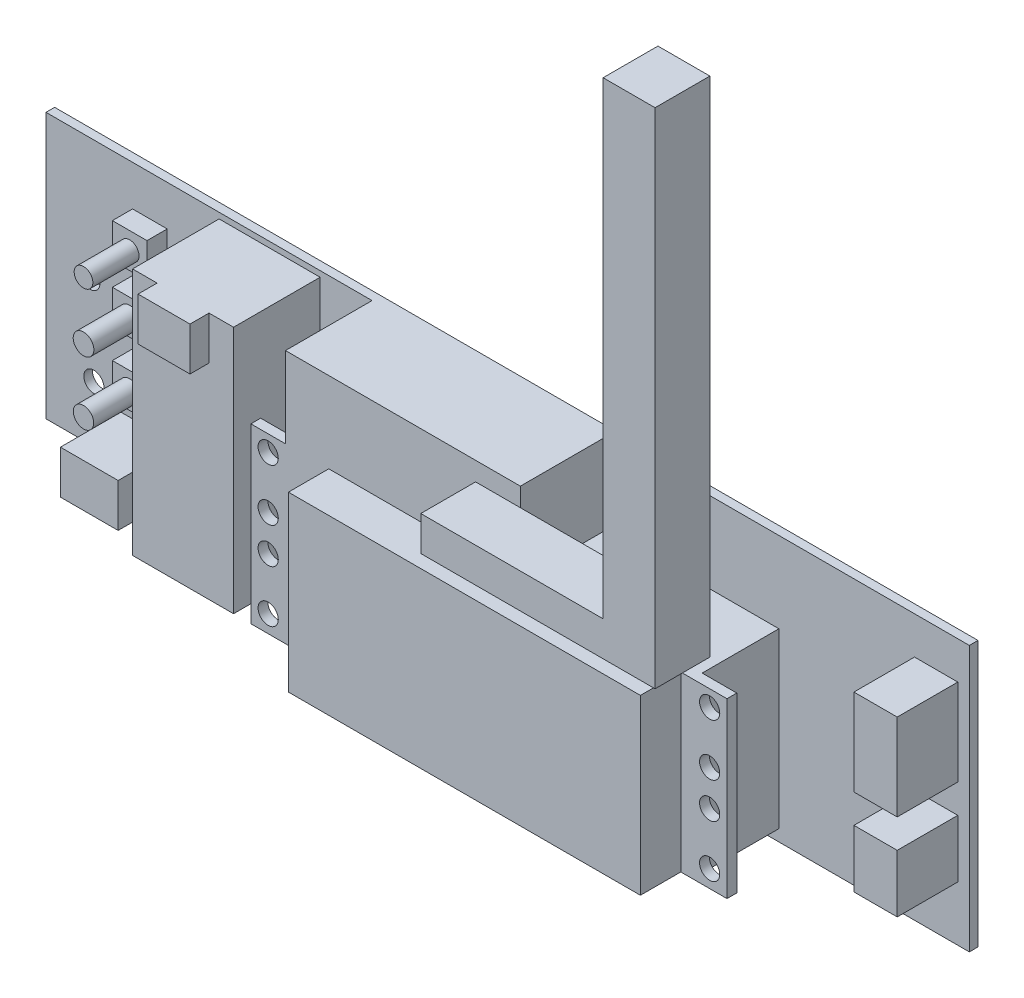
SolidWorks part; units mm, degrees
ref_plane "Přední rovina" through (0, 0, 0) normal (0, 0, 1) x (1, 0, 0)
ref_plane "Horní rovina" through (0, 0, 0) normal (0, 1, 0) x (1, 0, 0)
ref_plane "Pravá rovina" through (0, 0, 0) normal (1, 0, 0) x (0, 0, -1)
sketch "Skica1" plane through (0, 0, 0) normal (0, 0, 1) x (1, 0, 0)
  line L1 (-80, -23) -> (80, -23)
  line L2 (-80, -23) -> (-80, 23)
  line L3 (-80, 23) -> (80, 23)
  line L4 (80, -23) -> (80, 23)
  line L5 (-80, -23) -> (80, 23) construction
  line L6 (-80, 23) -> (80, -23) construction
  point P0 (0, 0)
  dimension "D1" = 160
  dimension "D2" = 46
extrude "Přidat vysunutím1" add sketch "Skica1" along normal blind 1.5
sketch "Skica2" plane through (0, 0, 1.5) normal (0, 0, 1) x (1, 0, 0)
  line L0 (-71.7, -23) -> (-71.7, 23) construction
  line L1 (-80, -23) -> (80, -23) construction
  line L2 (80, 23) -> (-80, 23) construction
  line L3 (62.7, 23) -> (62.7, -23) construction
  line L4 (-80, 23) -> (-80, -23) construction
  line L5 (80, -23) -> (80, 23) construction
  circle A0 centre (-71.7, -13.3) radius 1.75
  circle A1 centre (-72.4, 2) radius 1.75
  circle A2 centre (62.7, 3.2) radius 1.75
  circle A3 centre (62.7, -14.6) radius 1.75
  dimension "D1" = 3.5
  dimension "D2" = 8.3
  dimension "D3" = 7.6
  dimension "D4" = 9.7
  dimension "D5" = 25
  dimension "D6" = 17.3
  dimension "D7" = 8.4
  dimension "D8" = 26.2
extrude "Odebrat vysunutím1" cut sketch "Skica2" against normal through all both and the other way through all
sketch "Skica3" plane through (0, 0, 1.5) normal (0, 0, 1) x (1, 0, 0)
  line L0 (-80, -23) -> (80, -23) construction
  line L1 (-67, -23) -> (-57, -23)
  line L2 (-67, -23) -> (-67, -15.5)
  line L3 (-67, -15.5) -> (-57, -15.5)
  line L4 (-57, -23) -> (-57, -15.5)
  line L5 (80, -23) -> (80, 23) construction
  line L6 (78, -13.5) -> (70.5, -13.5)
  line L7 (78, -13.5) -> (78, -3.5)
  line L8 (78, -3.5) -> (70.5, -3.5)
  line L9 (70.5, -13.5) -> (70.5, -3.5)
  line L10 (78, 1.5) -> (70.5, 1.5)
  line L11 (78, 1.5) -> (78, 16.5)
  line L12 (78, 16.5) -> (70.5, 16.5)
  line L13 (70.5, 1.5) -> (70.5, 16.5)
  dimension "D1" = 7.5
  dimension "D2" = 10
  dimension "D3" = 13
  dimension "D4" = 7.5
  dimension "D5" = 7.5
  dimension "D6" = 10
  dimension "D7" = 15
  dimension "D8" = 9.5
  dimension "D9" = 24.5
  dimension "D10" = 2
extrude "Přidat vysunutím2" add sketch "Skica3" along normal blind 10.5
sketch "Skica5" plane through (0, 0, 1.5) normal (0, 0, 1) x (1, 0, 0)
  line L0 (-57, -23) -> (80, -23) construction
  line L1 (-65, -5) -> (-59, -5)
  line L2 (-65, -5) -> (-65, -11)
  line L3 (-65, -11) -> (-59, -11)
  line L4 (-59, -5) -> (-59, -11)
  line L5 (-65, 6) -> (-59, 6)
  line L6 (-65, 6) -> (-65, 0)
  line L7 (-65, 0) -> (-59, 0)
  line L8 (-59, 6) -> (-59, 0)
  line L9 (-65, 16) -> (-59, 16)
  line L10 (-65, 16) -> (-65, 10)
  line L11 (-65, 10) -> (-59, 10)
  line L12 (-59, 16) -> (-59, 10)
  line L13 (-80, 23) -> (-80, -23) construction
  dimension "D2" = 6
  dimension "D3" = 12
  dimension "D4" = 23
  dimension "D5" = 33
  dimension "D8" = 15
extrude "Přidat vysunutím3" add sketch "Skica5" along normal blind 3.5
sketch "Skica6" plane through (0, 0, 5) normal (0, 0, 1) x (1, 0, 0)
  line L0 (-65, 16) -> (-59, 10) construction
  line L1 (-65, 10) -> (-59, 16) construction
  line L2 (-65, 13) -> (-59, 13) construction
  line L3 (-65, 16) -> (-65, 10) construction
  line L4 (-59, 10) -> (-59, 16) construction
  line L5 (-62, 16) -> (-62, 10) construction
  line L6 (-59, 16) -> (-65, 16) construction
  line L7 (-65, 10) -> (-59, 10) construction
  line L8 (-62, 13) -> (-62, -23.1285) construction
  line L9 (-65, -8) -> (-59, -8) construction
  line L10 (-65, -5) -> (-65, -11) construction
  line L11 (-59, -11) -> (-59, -5) construction
  line L12 (-65, 3) -> (-59, 3) construction
  line L13 (-65, 6) -> (-65, 0) construction
  line L14 (-59, 0) -> (-59, 6) construction
  circle A0 centre (-62, 13) radius 1.6204
  circle A1 centre (-62, 3) radius 1.79
  circle A2 centre (-62, -8) radius 1.7657
  point P26 (-62, 13)
extrude "Přidat vysunutím4" add sketch "Skica6" along normal blind 8
sketch "Skica7" plane through (0, 0, 1.5) normal (0, 0, 1) x (1, 0, 0)
  line L0 (-80, 23) -> (-80, -23) construction
  line L1 (-50, -21) -> (-32.5, -21)
  line L2 (-50, -21) -> (-50, 22)
  line L3 (-50, 22) -> (-32.5, 22)
  line L4 (-32.5, -21) -> (-32.5, 22)
  line L5 (-23.5, 9) -> (47, 9)
  line L6 (-23.5, 9) -> (-23.5, -21)
  line L7 (-23.5, -21) -> (47, -21)
  line L8 (47, 9) -> (47, -21)
  line L9 (-57, -23) -> (80, -23) construction
  line L11 (-23.5, 9) -> (17.2, 9)
  line L12 (-23.5, 9) -> (-23.5, 23.5)
  line L13 (-23.5, 23.5) -> (17.2, 23.5)
  line L14 (17.2, 9) -> (17.2, 23.5)
  line M21 (80, 23) -> (-80, 23)
  dimension "D1" = 43
  dimension "D2" = 17.5
  dimension "D3" = 30
  dimension "D4" = 70.5
  dimension "D5" = 30
  dimension "D6" = 56.5
  dimension "D7" = 2
  dimension "D8" = 2
  dimension "D9" = 40.7
  dimension "D10" = 14.5
extrude "Přidat vysunutím5" add sketch "Skica7" along normal blind 15 contours L1 L4 L3 L2 | L8 L5 L6 L7 | L5 L14 L12 M21
sketch "Skica8" plane through (0, 0, 16.5) normal (0, 0, 1) x (1, 0, 0)
  line L0 (-50, 22) -> (-32.5, 22) construction
  line L1 (-45.75, 22) -> (-36.75, 22)
  line L2 (-45.75, 22) -> (-45.75, 14.5)
  line L3 (-45.75, 14.5) -> (-36.75, 14.5)
  line L4 (-36.75, 22) -> (-36.75, 14.5)
  line L5 (-41.25, 22) -> (-41.25, 16.6364) construction
  point P8 (-41.25, 22)
  dimension "D1" = 9
  dimension "D2" = 7.5
extrude "Přidat vysunutím6" add sketch "Skica8" along normal blind 3.3
sketch "Skica13" plane through (0, 0, 16.5) normal (0, 0, 1) x (1, 0, 0)
  line L1 (9.4389, 19.7615) -> (50.0389, 19.7615)
  line L2 (9.4389, 19.7615) -> (9.4389, 13.7615)
  line L3 (9.4389, 13.7615) -> (50.0389, 13.7615)
  line L4 (50.0389, 19.7615) -> (50.0389, 13.7615)
  line L5 (50.0389, 13.7615) -> (41.0389, 13.7615)
  line L6 (50.0389, 13.7615) -> (50.0389, 100.9615)
  line L7 (50.0389, 100.9615) -> (41.0389, 100.9615)
  line L8 (41.0389, 13.7615) -> (41.0389, 100.9615)
  line M7 (17.2, 9) -> (17.2, 23)
  dimension "D1" = 6
  dimension "D2" = 40.6
  dimension "D3" = 9
  dimension "D4" = 87.2
extrude "Přidat vysunutím7" add sketch "Skica13" along normal blind 9.5 contours L3 L8 L1 M7 | L8 L3 L4 L1 | L8 L1 L6 L7 | L2 L3 L1 M7
sketch "Skica14" plane through (0, 0, 16.5) normal (0, 0, 1) x (1, 0, 0)
  line L0 (-23.5, -21) -> (47, -21) construction
  line L1 (45, -21) -> (-16, -21)
  line L2 (45, -21) -> (45, 9)
  line L3 (45, 9) -> (-16, 9)
  line L4 (-16, -21) -> (-16, 9)
  line L5 (47, 9) -> (47, -21) construction
  dimension "D1" = 61
  dimension "D2" = 2
  dimension "D3" = 30
extrude "Přidat vysunutím8" add sketch "Skica14" along normal blind 7
sketch "Skica15" plane through (0, 0, 16.5) normal (0, 0, 1) x (1, 0, 0)
  line L8 (-23.5, 23) -> (-23.5, -21) construction
  line L10 (-23.5, -21) -> (-16, -21) construction
  line L11 (-29.5, 9) -> (-23.5, 9)
  line L12 (-29.5, 9) -> (-29.5, -21)
  line L13 (-29.5, -21) -> (-23.5, -21)
  line L14 (-23.5, 9) -> (-23.5, -21)
  line L15 (53, -21) -> (47, -21)
  line L16 (53, -21) -> (53, 9)
  line L17 (53, 9) -> (47, 9)
  line L18 (47, -21) -> (47, 9)
  line L19 (50, -18) -> (-26.5, -18) construction
  line L20 (50, -9) -> (-26.5, -9) construction
  line L21 (50, -2.8) -> (-27.5395, -2.8) construction
  line L22 (50, 6.2) -> (-26.8047, 6.2) construction
  circle A0 centre (-26.5, -18) radius 1.75
  circle A1 centre (-26.5, 6.2) radius 1.75
  circle A2 centre (50, -18) radius 1.75
  circle A3 centre (50, -9) radius 1.75
  circle A4 centre (50, -2.8) radius 1.75
  circle A5 centre (50, 6.2) radius 1.75
  circle A6 centre (-26.5, -9) radius 1.75
  circle A7 centre (-26.5, -2.8) radius 1.75
  dimension "D5" = 3.5
  dimension "D1" = 30
  dimension "D2" = 6
  dimension "D3" = 6
  dimension "D4" = 30
  dimension "D6" = 3
  dimension "D7" = 12
  dimension "D8" = 18.2
  dimension "D9" = 27.2
  dimension "D10" = 3
  dimension "D11" = 76.5
extrude "Přidat vysunutím9" add sketch "Skica15" against normal blind 1.7
sketch "Skica16" plane through (0, 22, 0) normal (0, 1, 0) x (1, 0, 0)
  line L0 (-36.75, -16.5) -> (-45.75, -16.5) construction
  line L1 (-41.25, -16.5) -> (-41.25, -19.8) construction
  line L2 (-36.75, -19.8) -> (-45.75, -19.8) construction
  line L3 (-36.75, -18.15) -> (-45.75, -18.15) construction
  line L4 (-36.75, -19.8) -> (-36.75, -16.5) construction
  line L5 (-45.75, -19.8) -> (-45.75, -16.5) construction
  point P14 (-41.25, -18.15)
